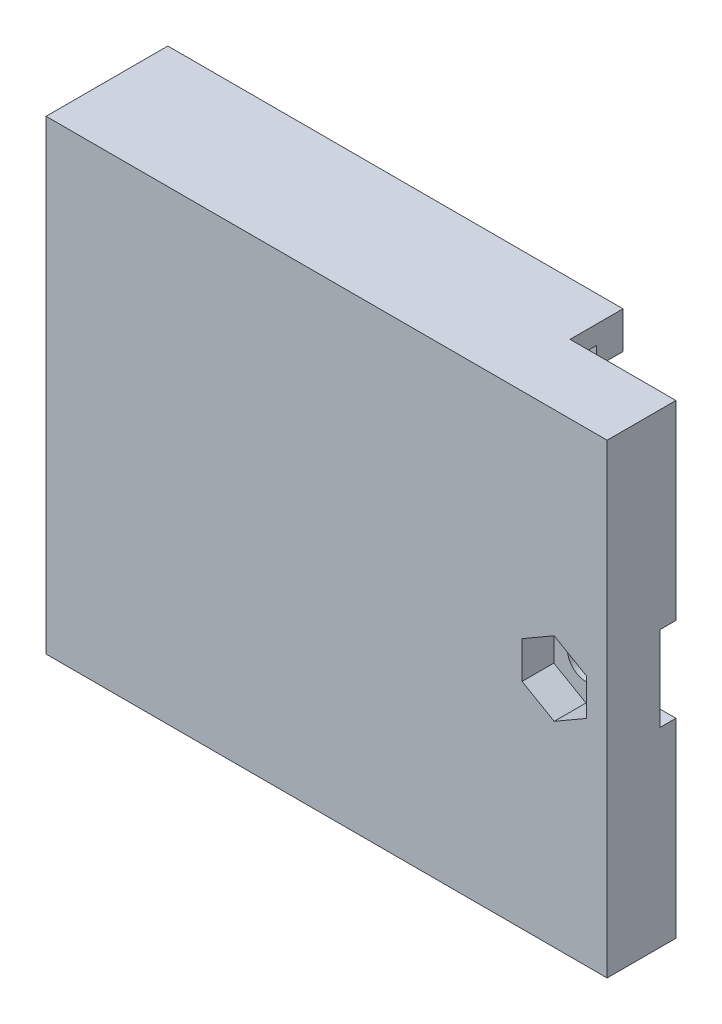
SolidWorks part; units mm, degrees
ref_plane "Alzado" through (0, 0, 0) normal (0, 0, 1) x (1, 0, 0)
ref_plane "Planta" through (0, 0, 0) normal (0, 1, 0) x (1, 0, 0)
ref_plane "Vista lateral" through (0, 0, 0) normal (1, 0, 0) x (0, 0, -1)
sketch "Croquis1" plane through (0, 0, 0) normal (0, 0, 1) x (1, 0, 0)
  line L1 (-26.5, 22) -> (26.5, 22)
  line L2 (-26.5, 22) -> (-26.5, -22)
  line L3 (-26.5, -22) -> (26.5, -22)
  line L4 (26.5, 22) -> (26.5, -22)
  line L5 (-26.5, 22) -> (26.5, -22) construction
  line L6 (-26.5, -22) -> (26.5, 22) construction
  circle A0 centre (21.5, 0) radius 1.75
  point P0 (0, 0)
  dimension "D4" = 3.5
  dimension "D1" = 44
  dimension "D2" = 53
  dimension "D3" = 5
extrude "Saliente-Extruir1" add sketch "Croquis1" along normal blind 6.5
sketch "Croquis3" plane through (0, 0, 0) normal (0, 0, -1) x (-1, 0, 0)
  line L0 (-16.5, -22) -> (-16.5, -20.25)
  line L1 (26.5, -22) -> (-26.5, -22) construction
  line L2 (-16.5, -20.25) -> (26.5, -20.25)
  line L3 (26.5, 22) -> (26.5, -22) construction
  line L4 (26.5, -20.25) -> (26.5, -22)
  line L5 (26.5, -22) -> (-16.5, -22)
  line L6 (-26.5, -22) -> (-26.5, 22) construction
  line L7 (26.5, 22) -> (-16.5, 22)
  line L8 (-26.5, 22) -> (26.5, 22) construction
  line L9 (-16.5, 22) -> (-16.5, 20.25)
  line L10 (-16.5, 20.25) -> (26.5, 20.25)
  line L11 (26.5, 20.25) -> (26.5, 22)
  dimension "D1" = 10
  dimension "D2" = 1.75
extrude "Saliente-Extruir2" add sketch "Croquis3" along normal blind 5
sketch "Croquis4" plane through (0, 0, -5) normal (0, 0, -1) x (-1, 0, 0)
  line L0 (-16.5, -20.25) -> (26.5, -20.25)
  line L1 (26.5, -20.25) -> (26.5, -18.5)
  line L2 (26.5, 20.25) -> (26.5, -20.25) construction
  line L3 (26.5, -18.5) -> (-16.5, -18.5)
  line L4 (-16.5, -18.5) -> (-16.5, -20.25)
  line L5 (-16.5, 20.25) -> (-16.5, 18.5)
  line L6 (-16.5, 18.5) -> (26.5, 18.5)
  line L7 (26.5, 18.5) -> (26.5, 20.25)
  line L8 (26.5, 20.25) -> (-16.5, 20.25)
  dimension "D1" = 1.75
  dimension "D2" = 1.75
extrude "Saliente-Extruir3" add sketch "Croquis4" against normal blind 2.5
sketch "Croquis5" plane through (0, 0, 0) normal (0, 0, -1) x (-1, 0, 0)
  line L0 (26.5, -4) -> (26.5, 4)
  line L1 (26.5, 20.25) -> (26.5, -20.25) construction
  line L2 (26.5, -4) -> (-26.5, -4)
  line L3 (-26.5, -4) -> (-26.5, 4)
  line L4 (-26.5, 4) -> (26.5, 4)
  point P4 (26.5, 0)
  dimension "D1" = 8
  dimension "D2" = 53
extrude "Cortar-Extruir2" cut sketch "Croquis5" against normal blind 1.5
sketch "Croquis8" plane through (0, 0, 1.5) normal (0, 0, -1) x (-1, 0, 0)
  line L0 (26.5, -4) -> (26.5, 4)
  line L1 (26.5, 4) -> (24.5, 4)
  line L2 (26.5, 4) -> (-26.5, 4) construction
  line L3 (24.5, 4) -> (24.5, -4)
  line L4 (-26.5, -4) -> (26.5, -4) construction
  line L5 (24.5, -4) -> (26.5, -4)
  dimension "D1" = 2
extrude "Saliente-Extruir6" add sketch "Croquis8" along normal blind 3
sketch "Croquis9" plane through (0, 4, 0) normal (0, -1, 0) x (1, 0, 0)
  line L0 (-24.5, 1.5) -> (-18.5, 1.5)
  line L1 (-24.5, 1.5) -> (26.5, 1.5) construction
  line L2 (-18.5, 1.5) -> (-24.5, 0.75)
  line L3 (-24.5, 0) -> (-24.5, 1.5) construction
  line L4 (-24.5, 0.75) -> (-24.5, 1.5)
  dimension "D1" = 6
extrude "Saliente-Extruir7" add sketch "Croquis9" along normal up to surface (8 mm away) up to face at (1, -4, 0.75)
sketch "Croquis10" plane through (0, 0, 6.5) normal (0, 0, 1) x (1, 0, 0)
  line L1 (21.5, -3.5) -> (24.5311, -1.75)
  line L2 (24.5311, -1.75) -> (24.5311, 1.75)
  line L3 (24.5311, 1.75) -> (21.5, 3.5)
  line L4 (21.5, 3.5) -> (18.4689, 1.75)
  line L5 (18.4689, 1.75) -> (18.4689, -1.75)
  line L6 (18.4689, -1.75) -> (21.5, -3.5)
  circle A0 centre (21.5, 0) radius 3.0311 construction
  dimension "D1" = 7
extrude "Cortar-Extruir3" cut sketch "Croquis10" against normal blind 3
